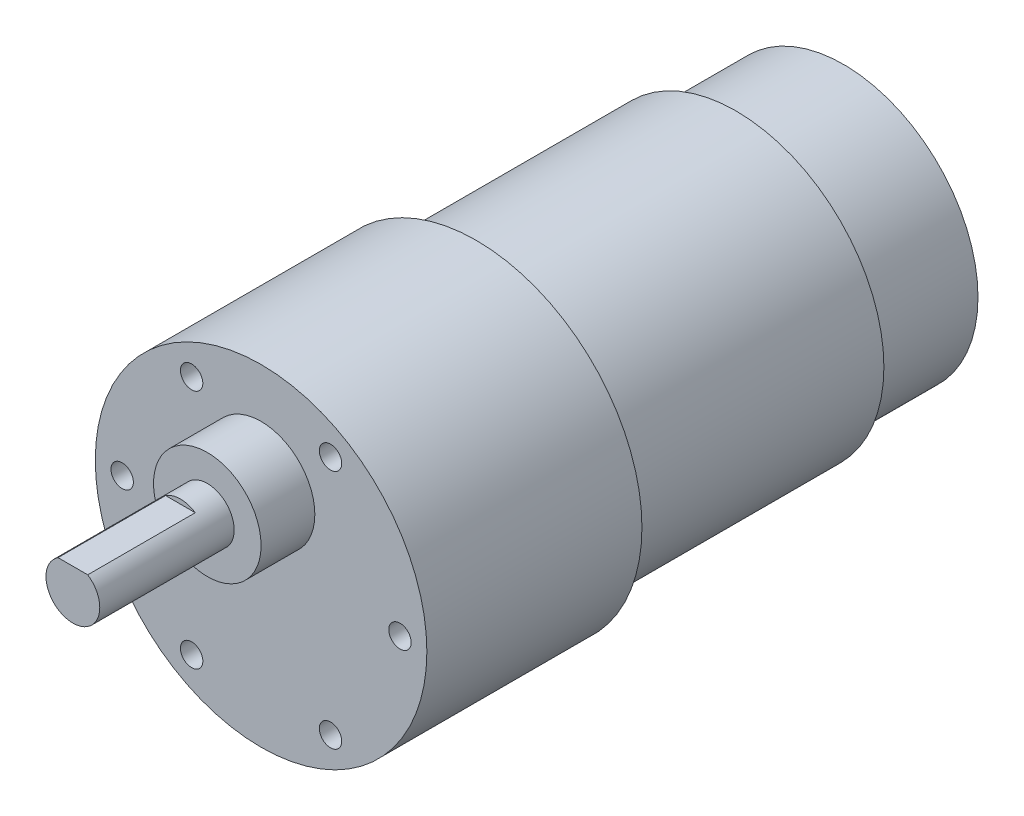
SolidWorks part; units mm, degrees
ref_plane "前视基准面" through (0, 0, 0) normal (0, 0, 1) x (1, 0, 0)
ref_plane "上视基准面" through (0, 0, 0) normal (0, 1, 0) x (1, 0, 0)
ref_plane "右视基准面" through (0, 0, 0) normal (1, 0, 0) x (0, 0, -1)
other "Configuration Table"
sketch "Profile_1" plane through (0, 0, 0) normal (0, 0, 1) x (1, 0, 0)
  circle A0 centre (0, -7) radius 18.5
extrude "Gearbox" add sketch "Profile_1" along normal blind 24 from offset 24
sketch "Profile_2" plane through (0, 0, 0) normal (0, 0, 1) x (1, 0, 0)
  circle A0 centre (15.5, -7) radius 1.25
  circle A1 centre (7.75, 6.4234) radius 1.25
  circle A2 centre (-7.75, 6.4234) radius 1.25
  circle A3 centre (-15.5, -7) radius 1.25
  circle A4 centre (-7.75, -20.4234) radius 1.25
  circle A5 centre (7.75, -20.4234) radius 1.25
extrude "Thread_pilots" cut sketch "Profile_2" along normal blind 3.51 from offset 3.5
sketch "Profile_3" plane through (0, 0, 0) normal (0, 0, 1) x (1, 0, 0)
  circle A0 centre (0, -7) radius 16.5
extrude "Armature" add sketch "Profile_3" along normal blind 29 from offset 53
sketch "Profile_4" plane through (0, 0, 0) normal (0, 0, 1) x (1, 0, 0)
  circle A0 centre (0, -7) radius 15
extrude "Encoder_envelope" add sketch "Profile_4" along normal blind 12 from offset 65
sketch "Profile_5" plane through (0, 0, 0) normal (0, 0, 1) x (1, 0, 0)
  circle A0 centre (0, 0) radius 6
extrude "Nose" add sketch "Profile_5" along normal blind 6 from offset 0
sketch "Profile_6" plane through (0, 0, 0) normal (0, 0, 1) x (1, 0, 0)
  circle A0 centre (0, 0) radius 3
extrude "Output" add sketch "Profile_6" along normal blind 15 from offset 6
sketch "Profile_7" plane through (0, 0, 0) normal (0, 0, 1) x (1, 0, 0)
  line L0 (-4, 2.5) -> (4, 2.5)
  line L1 (4, 2.5) -> (4, 4)
  line L2 (4, 4) -> (-4, 4)
  line L3 (-4, 4) -> (-4, 2.5)
extrude "D_flat" cut sketch "Profile_7" along normal blind 12.01 from offset 9
